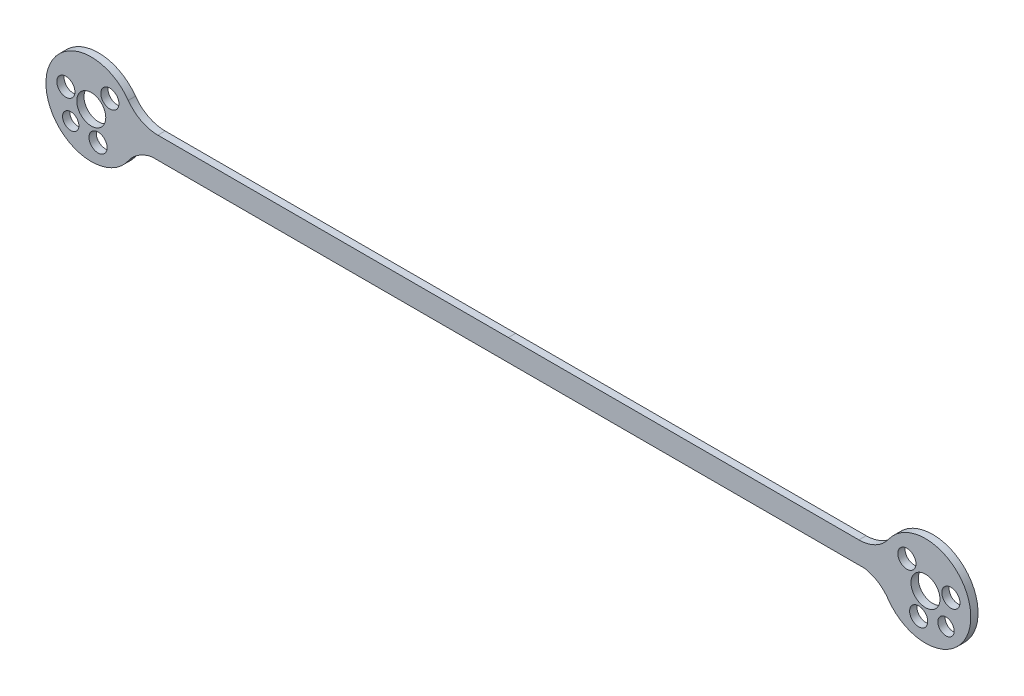
SolidWorks part; units mm, degrees
material "Thornel Mat VMA"
ref_plane "前视基准面" through (0, 0, 0) normal (0, 0, 1) x (1, 0, 0)
ref_plane "上视基准面" through (0, 0, 0) normal (0, 1, 0) x (1, 0, 0)
ref_plane "右视基准面" through (0, 0, 0) normal (1, 0, 0) x (0, 0, -1)
sketch "草图1" plane through (0, 0, 0) normal (0, 0, 1) x (1, 0, 0)
  line L0 (-97.3335, -2.5697) -> (0.9213, -2.5696)
  line L1 (0.9213, -2.5696) -> (99.1761, -2.5695)
  line L2 (97.557, 3.4305) -> (0.9213, 3.4304)
  line L3 (0.9213, 3.4304) -> (-95.7144, 3.4303)
  arc A0 (-97.3335, -2.5697) -> (-103.8179, -6.7087) centre (-95.6093, -12.4199) ccw
  arc A1 (105.6605, -6.7084) -> (99.1761, -2.5695) centre (97.4519, -12.4197) ccw
  arc A2 (105.6605, -6.7084) -> (105.7189, 7.6527) centre (115.9212, 0.4306) ccw
  arc A3 (97.557, 3.4305) -> (105.7189, 7.6527) centre (97.557, 13.4305) ccw
  arc A4 (-103.8763, 7.6525) -> (-95.7144, 3.4303) centre (-95.7144, 13.4303) ccw
  arc A5 (-103.8763, 7.6525) -> (-103.8179, -6.7087) centre (-114.0786, 0.4303) ccw
  circle A6 centre (-119.7356, -5.2264) radius 2.25
  circle A7 centre (-121.0817, 2.3069) radius 2.5
  circle A8 centre (-108.9522, 5.5569) radius 2.5
  circle A9 centre (-112.2023, -6.5725) radius 2.5
  circle A10 centre (-114.0786, 0.4303) radius 4
  circle A11 centre (115.9212, 0.4306) radius 4
  circle A12 centre (110.7948, 5.5569) radius 2.5
  circle A13 centre (122.9242, 2.3069) radius 2.5
  circle A14 centre (121.5781, -5.2264) radius 2.25
  circle A15 centre (114.0448, -6.5725) radius 2.5
  dimension "D1" = 6
extrude "凸台-拉伸1" add sketch "草图1" along normal blind 2
